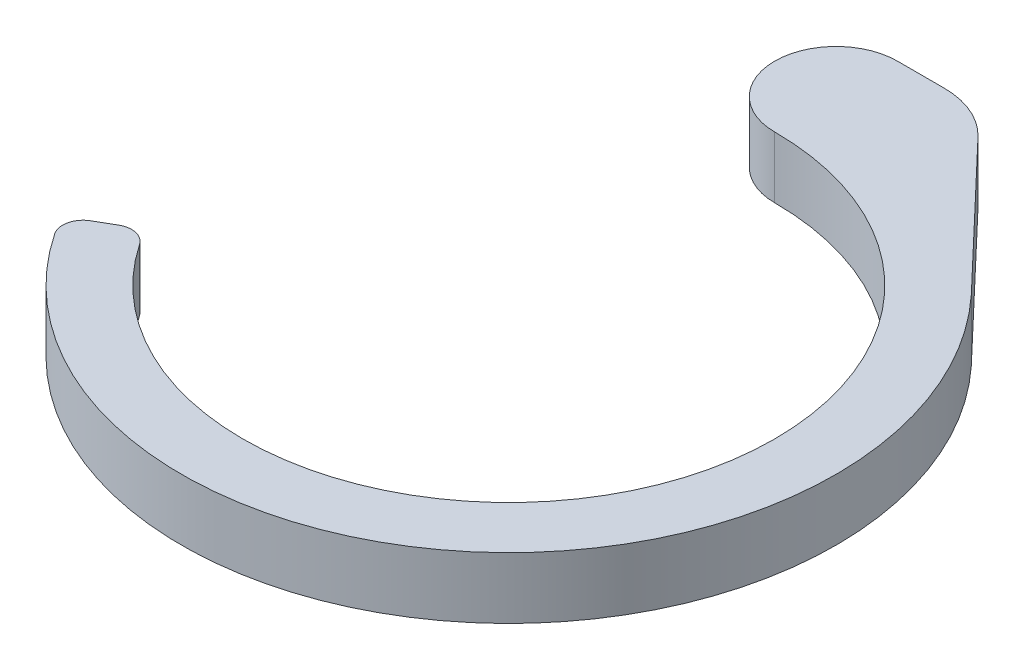
SolidWorks part; units mm, degrees
ref_plane "正面" through (0, 0, 0) normal (0, 0, 1) x (1, 0, 0)
ref_plane "平面" through (0, 0, 0) normal (0, 1, 0) x (1, 0, 0)
ref_plane "右側面" through (0, 0, 0) normal (1, 0, 0) x (0, 0, -1)
sketch "ｽｹｯﾁ2" plane through (0, 0, 0) normal (0, 1, 0) x (1, 0, 0)
  line L1 (-1.8089, 2.6033) -> (0, 0)
  line L2 (-60.4669, -34.9106) -> (-64.8074, -37.4166)
  line L4 (0, 95) -> (11.4274, 95)
  line L5 (25.9115, 88.7917) -> (58.5757, 54.4875)
  arc A0 (-66.4612, -44.5298) -> (57.2894, 55.8384) centre (0, 0) ccw
  arc A1 (-53.8264, -36.4378) -> (0, 65) centre (0, 0) ccw
  arc A2 (0, 95) -> (0, 65) centre (0, 80) ccw
  arc A3 (11.4274, 95) -> (25.9115, 88.7917) centre (11.4274, 75) cw
  arc A4 (-53.8264, -36.4378) -> (-60.4669, -34.9106) centre (-57.9669, -39.2407) ccw
  arc A5 (-66.4612, -44.5298) -> (-64.8074, -37.4166) centre (-62.3074, -41.7467) cw
  dimension "D1" = 160
  dimension "D2" = 130
  dimension "D4" = 20
  dimension "D5" = 5
  dimension "D6" = 5
extrude "ﾎﾞｽ - 押し出し4" add sketch "ｽｹｯﾁ2" along normal blind 15 contours A5 A0 L5 A3 L4 A2 A1 A4 L2
